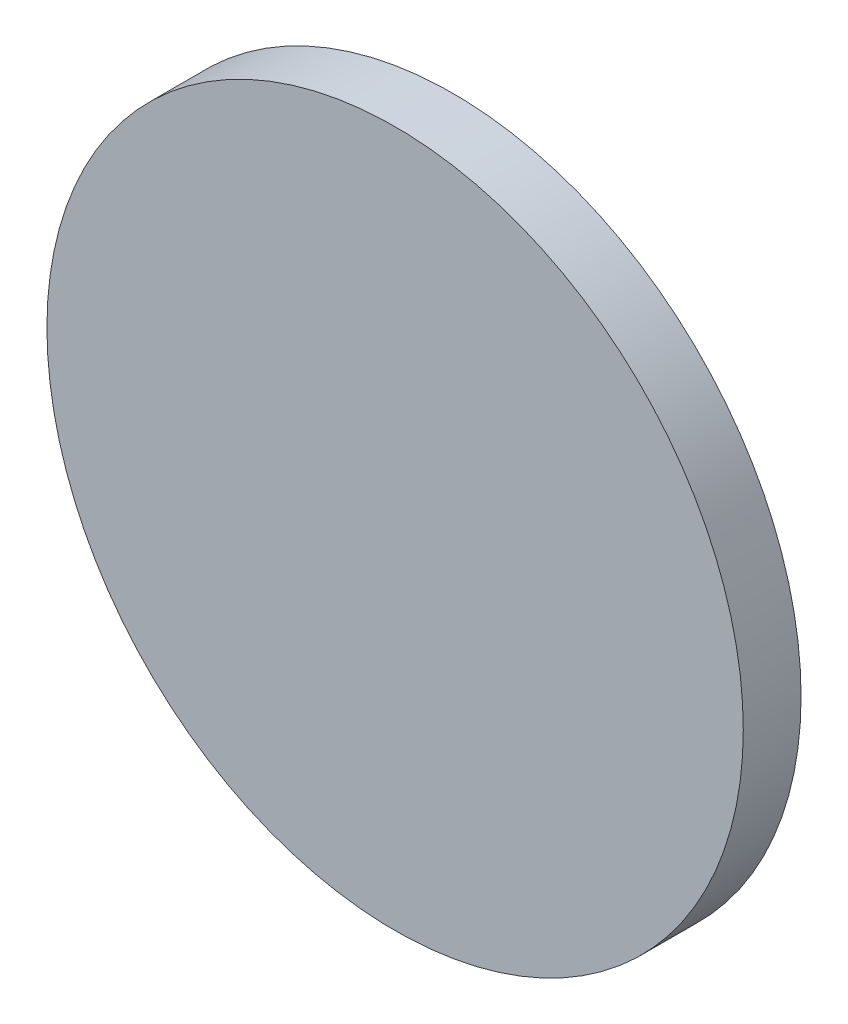
SolidWorks part; units mm, degrees
ref_plane "Спереди" through (0, 0, 0) normal (0, 0, 1) x (1, 0, 0)
ref_plane "Сверху" through (0, 0, 0) normal (0, 1, 0) x (1, 0, 0)
ref_plane "Справа" through (0, 0, 0) normal (1, 0, 0) x (0, 0, -1)
sketch "Эскиз1" plane through (0, 0, 0) normal (0, 0, 1) x (1, 0, 0)
  circle A0 centre (-58.1454, 33.859) radius 301.2043
extrude "Бобышка-Вытянуть1" add sketch "Эскиз1" along normal blind 50
